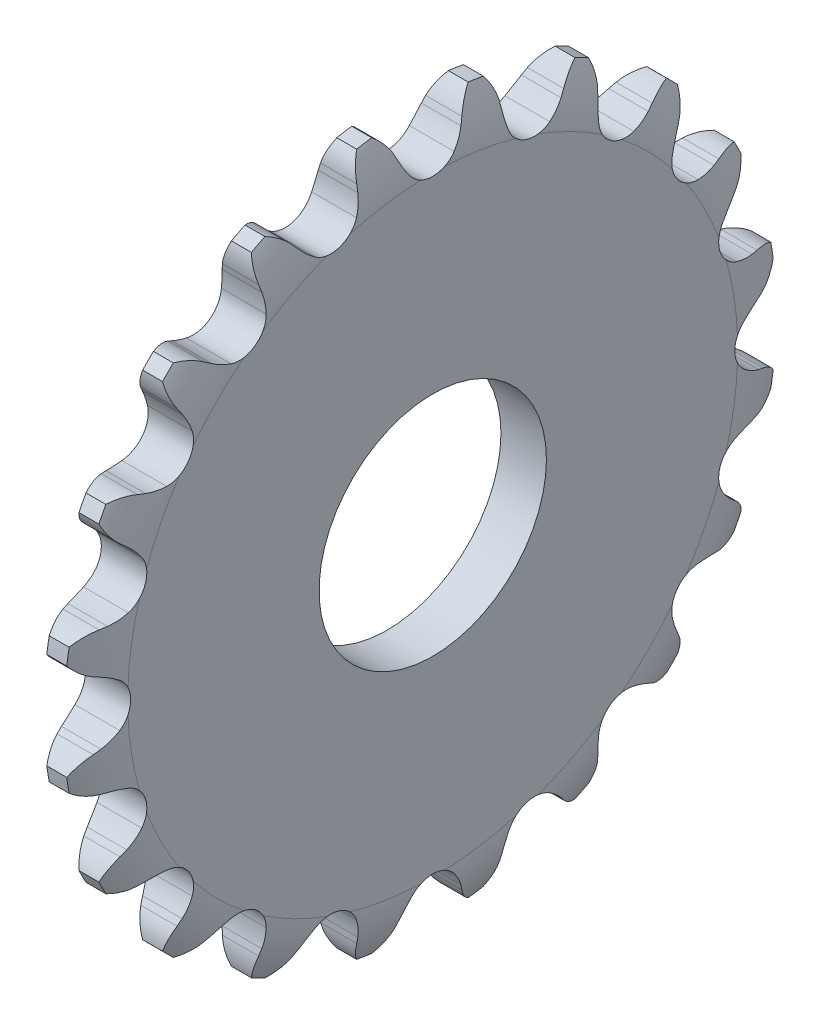
SolidWorks part; units mm, degrees
ref_plane "Plane1" through (0, 0, 0) normal (0, 0, 1) x (1, 0, 0)
ref_plane "Plane2" through (0, 0, 0) normal (0, 1, 0) x (1, 0, 0)
ref_plane "Plane3" through (0, 0, 0) normal (1, 0, 0) x (0, 0, -1)
other "Configuration Table"
sketch "Clipboard" plane through (0, 0, 0) normal (0, 1, 0) x (1, 0, 0)
  line L0 (0, 0) -> (5.967, -2.1718)
  line L1 (-15, 0) -> (100, 0) construction
  line L2 (0, 0) -> (-0.5218, 0.5897)
  line L3 (0, 0) -> (-2.9658, 1.1335)
  line L4 (0, 0) -> (2.9835, 1.0859)
  line L5 (0, 0) -> (-47.5972, -17.7524)
  line L6 (0, 0) -> (-2.3214, -1.5662)
  line L7 (-0.5218, 0.5897) -> (46.9042, 18.7948)
  line L8 (-76.2, 38.1) -> (-61.976, 38.1)
  line L9 (-73.2057, 38.5609) -> (-73.0533, 38.5634)
  line L10 (-73.0533, 76.1892) -> (-66.6525, 76.1892)
  circle A0 centre (0, 0) radius 1.651
  circle A1 centre (0, 0) radius 16.4902
  circle A2 centre (0, 0) radius 38.1
  dimension "Dr" = 3.302
  dimension "MHD" = 32.9803
  dimension "Hub_dia" = 76.2
  dimension "Num_teeth" = 20
  dimension "Pitch" = 6.35
  dimension "Width" = 3.175
  dimension "Chamfer_wid" = 0.7874
  dimension "Chamfer_dep" = 3.175
  dimension "Overall_len" = 50.8
  dimension "Show_teeth" = 20
  dimension "Thickness" = 2.8003
  dimension "OAL" = 50.8001
  dimension "T_dim" = 14.224
  dimension "Width_const" = 0.1524
  dimension "Width_factor" = 0.93
  dimension "Num_strands" = 1
  dimension "Transv_pitch" = 6.4008
sketch "BasProSke" plane through (0, 0, 0) normal (0, 1, 0) x (1, 0, 0)
  line L0 (-10, 0) -> (60, 0) construction
  line L1 (0, 0) -> (0, 18.7762)
  line L2 (0, 0) -> (2.8003, 0)
  line L3 (2.8003, 0) -> (2.8003, 18.7762)
  line L4 (2.0129, 21.9512) -> (0.7874, 21.9512)
  arc A0 (0, 18.7762) -> (0.7874, 21.9512) centre (6.7949, 18.7762) cw
  arc A1 (2.8003, 18.7762) -> (2.0129, 21.9512) centre (-3.9946, 18.7762) ccw
  dimension "Thickness" = 2.8003
  dimension "D1" = 6.7949
  dimension "G1" = 0.7874
  dimension "G2" = 0.7874
  dimension "H2" = 3.175
  dimension "H1" = 3.175
  dimension "Diameter" = 43.9023
revolve "Base-Revolve" add sketch "BasProSke" angle 360 about L0
sketch "GrvSke" plane through (0, 0, 0) normal (0, 1, 0) x (1, 0, 0)
  line L0 (2.8003, 18.7762) -> (2.8003, 16.4902)
  line L1 (2.8003, 16.4902) -> (6.4008, 16.4902)
  line L2 (6.4008, 16.4902) -> (6.4008, 18.7762)
  line L3 (2.0129, 21.9512) -> (7.1882, 21.9512)
  line L4 (4.6006, 0) -> (4.6006, 52.07) construction
  line L5 (-10, 0) -> (60, 0) construction
  line L6 (0, 0) -> (35.56, 0) construction
  arc A0 (6.4008, 18.7762) -> (7.1882, 21.9512) centre (13.1957, 18.7762) cw
  arc A1 (2.8003, 18.7762) -> (2.0129, 21.9512) centre (-3.9946, 18.7762) ccw
  dimension "G1" = 0.7874
  dimension "H1" = 3.175
  dimension "Diameter" = 43.9023
  dimension "Grv_diam" = 32.9803
  dimension "Grv_width" = 3.6004
  dimension "Offset" = 4.6006
revolve "Groove" [suppressed] cut sketch "GrvSke" angle 360 about L6
pattern_linear "Grooves" [suppressed]
sketch "TooCutSke" plane through (0, 0, 0) normal (1, 0, 0) x (0, 0, -1)
  line L0 (1.9183, 20.241) -> (2.0772, 20.619)
  line L1 (0, 0) -> (0, 107) construction
  line L2 (0, 20.296) -> (-10, 20.296) construction
  line L3 (-1.9183, 20.241) -> (-2.0772, 20.619)
  arc A0 (1.3375, 19.251) -> (1.9183, 20.241) centre (-2.0816, 21.9224) ccw
  arc A1 (1.3375, 19.251) -> (-1.3375, 19.251) centre (0, 20.296) cw
  arc A2 (2.0772, 20.619) -> (4.5659, 22.2725) centre (4.5659, 19.5729) cw
  arc A3 (-1.3375, 19.251) -> (-1.9183, 20.241) centre (2.0816, 21.9224) cw
  arc A4 (-2.0772, 20.619) -> (-4.5659, 22.2725) centre (-4.5659, 19.5729) ccw
  arc A5 (4.5659, 22.2725) -> (-4.5659, 22.2725) centre (0, 0) ccw
  dimension "R" = 1.6974
  dimension "E" = 4.339
  dimension "F" = 2.6996
  dimension "Pitch_radius" = 20.296
  dimension "W" = 4.5659
  dimension "V" = 0.7232
  dimension "A" = 38
  dimension "B" = 15.2
extrude "ToothCut" cut sketch "TooCutSke" along normal through all
pattern_circular "TeethCuts" count 20 every 18 about axis through (-10, 0, 0) along (1, 0, 0) of "ToothCut"
sketch "HubNeaOneSke" plane through (0, 0, 0) normal (-1, 0, 0) x (0, 0, 1)
  circle A0 centre (0, 0) radius 16.4902
  dimension "Diameter" = 32.9803
extrude "HubNearOne" [suppressed] add sketch "HubNeaOneSke" along normal blind 47.9997
sketch "HubNeaBotSke" plane through (0, 0, 0) normal (-1, 0, 0) x (0, 0, 1)
  circle A0 centre (0, 0) radius 16.4902
  dimension "Diameter" = 32.9803
extrude "HubNearBoth" [suppressed] add sketch "HubNeaBotSke" along normal blind 23.9999
ref_plane "FarPln" through (2.8003, 0, 0) normal (1, 0, 0) x (0, 0, -1)
sketch "HubFarSke" plane through (2.8003, 0, 0) normal (1, 0, 0) x (0, 0, -1)
  circle A0 centre (0, 0) radius 16.4902
  dimension "Diameter" = 32.9803
extrude "HubFar" [suppressed] add sketch "HubFarSke" along normal blind 23.9999
sketch "BorSke" plane through (0, 0, 0) normal (1, 0, 0) x (0, 0, -1)
  circle A0 centre (0, 0) radius 6.35
  dimension "Diameter" = 12.7
extrude "Bore" cut sketch "BorSke" along normal mid plane 101.6001
sketch "KeySke" plane through (0, 0, 0) normal (1, 0, 0) x (0, 0, -1)
  line L0 (-1.5875, 0) -> (-1.5875, 7.874)
  line L1 (-1.5875, 7.874) -> (1.5875, 7.874)
  line L2 (1.5875, 7.874) -> (1.5875, 0)
  line L3 (0, 0) -> (0, 34) construction
  line L4 (-1.5875, 0) -> (1.5875, 0)
  dimension "Width" = 3.175
  dimension "Offset" = 7.874
extrude "Keyway" [suppressed] cut sketch "KeySke" along normal mid plane 101.6001
pattern_circular "Keyway2" [suppressed] count 2 every 90 about axis through (-10, 0, 0) along (1, 0, 0)
sketch "Sketch1" plane through (0, 0, 0) normal (1, 0, 0) x (0, 0, -1)
  circle A0 centre (0, 0) radius 7
extrude "Bore 14 mm" cut sketch "Sketch1" against normal through all both and the other way through all both
equation "\"Num_teeth@Clipboard\" = int( \"Num_teeth@Clipboard\" )"
equation "\"Num_teeth@Clipboard\" = ((sgn( \"Num_teeth@Clipboard\" - 5.0)+1)*( \"Num_teeth@Clipboard\" - 5.0))/2 +5.0"
equation "\"Num_teeth@Clipboard\" = ((sgn( \"Num_teeth@Clipboard\" - 200.0)-1)*( \"Num_teeth@Clipboard\" - 200.0))/-2 +200.0"
equation "\"MHD@Clipboard\" = \"Pitch@Clipboard\" * (1.0 / tan(3.14159265 / \"Num_teeth@Clipboard\" ) - 1.0) - 0.03"
equation "\"Thickness@Clipboard\"  = \"Width@Clipboard\" * \"Width_factor@Clipboard\" - \"Width_const@Clipboard\" + (\"Num_strands@Clipboard\" - 1) * \"Transv_pitch@Clipboard\""
equation "\"OAL@Clipboard\" = \"Thickness@Clipboard\""
equation "\"MHD@Clipboard\" = ((sgn( \"MHD@Clipboard\" - \"Hub_dia@Clipboard\" )-1)*( \"MHD@Clipboard\" - \"Hub_dia@Clipboard\" ))/-2+ \"Hub_dia@Clipboard\""
equation "\"OAL@Clipboard\" = ((sgn( \"OAL@Clipboard\" - \"Overall_len@Clipboard\" )+1)*( \"OAL@Clipboard\" - \"Overall_len@Clipboard\" ))/2 + \"Overall_len@Clipboard\" + 0.000002"
equation "\"Num_teeth@TeethCuts\" = int( \"Show_teeth@Clipboard\" ) + 1"
equation "\"Num_teeth@TeethCuts\" = ((sgn( \"Num_teeth@TeethCuts\" - \"Num_teeth@Clipboard\" )-1)*( \"Num_teeth@TeethCuts\" - \"Num_teeth@Clipboard\" ))/-2+ \"Num_teeth@Clipboard\""
equation "\"Num_teeth@TeethCuts\" = ((sgn( \"Num_teeth@TeethCuts\" - 2.0)+1)*( \"Num_teeth@TeethCuts\" - 2.0))/2 +2.0"
equation "\"Angle@TeethCuts\" = 360.0 / \"Num_teeth@Clipboard\""
equation "\"Pitch_radius@TooCutSke\" = ( \"Pitch@Clipboard\" / 2.0) / sin(3.14159265 / \"Num_teeth@Clipboard\" )  'ma"
equation "\"R@TooCutSke\"  = \"Dr@Clipboard\" * 0.5025 + 0.0015"
equation "\"A@TooCutSke\" = 35.0 + (60.0 / \"Num_teeth@Clipboard\")"
equation "\"E@TooCutSke\"  = \"Dr@Clipboard\" * 1.3025 + 0.0015"
equation "\"B@TooCutSke\"  = 18.0 - (56.0 / \"Num_teeth@Clipboard\" )"
equation "\"W@TooCutSke\" = 1.4 * \"Dr@Clipboard\" * cos(3.14159265 / \"Num_teeth@Clipboard\" )"
equation "\"V@TooCutSke\" = 1.4 * \"Dr@Clipboard\" * sin(3.14159265 / \"Num_teeth@Clipboard\" )"
equation "\"Diameter@BasProSke\" = 2.0 * ( (0.3 * \"Pitch@Clipboard\" ) +  \"Pitch@Clipboard\" / 2.0 / tan(3.14159265 / \"Num_teeth@Clipboard\" ))"
equation "\"Thickness@BasProSke\"  = \"Thickness@Clipboard\""
equation "\"G1@BasProSke\" =  \"Chamfer_wid@Clipboard\""
equation "\"G2@BasProSke\" =  \"Chamfer_wid@Clipboard\""
equation "\"H1@BasProSke\" =  \"Chamfer_dep@Clipboard\""
equation "\"H2@BasProSke\" =  \"Chamfer_dep@Clipboard\""
equation "\"Diameter@GrvSke\" = \"Diameter@BasProSke\""
equation "\"G1@GrvSke\" = \"Chamfer_wid@Clipboard\""
equation "\"H1@GrvSke\" = \"Chamfer_dep@Clipboard\""
equation "\"Grv_diam@GrvSke\" =  \"Pitch@Clipboard\" * (1.0 / tan(3.14159265 / \"Num_teeth@Clipboard\" ) - 1.0) - 0.03"
equation "\"Grv_width@GrvSke\" =  \"Transv_pitch@Clipboard\" - ( \"Width@Clipboard\" * \"Width_factor@Clipboard\" - \"Width_const@Clipboard\" )"
equation "\"Offset@GrvSke\" = \"Grv_width@GrvSke\" / 2.0 + ( \"Width@Clipboard\" * \"Width_factor@Clipboard\" - \"Width_const@Clipboard\" )"
equation "\"Offset@Grooves\" = \"Transv_pitch@Clipboard\""
equation "\"Num_grvs@Grooves\" = \"Num_strands@Clipboard\""
equation "\"Num_grvs@Grooves\" = \"Num_grvs@Grooves\" - 1 * sgn( \"Num_grvs@Grooves\" -1)"
equation "\"Diameter@HubNeaOneSke\" = \"MHD@Clipboard\""
equation "\"Length@HubNearOne\" = \"OAL@Clipboard\" - \"Thickness@BasProSke\""
equation "\"Diameter@HubNeaBotSke\" = \"MHD@Clipboard\""
equation "\"Length@HubNearBoth\" = ( \"OAL@Clipboard\" - \"Thickness@BasProSke\" ) / 2.0"
equation "\"Thickness@FarPln\" = \"Thickness@BasProSke\""
equation "\"Diameter@HubFarSke\" = \"MHD@Clipboard\""
equation "\"Length@HubFar\" = ( \"OAL@Clipboard\" - \"Thickness@BasProSke\" ) / 2.0"
equation "\"D1@Bore\" = \"OAL@Clipboard\" * 2.0"
equation "\"D1@Keyway\" = \"OAL@Clipboard\" * 2.0"
equation "\"Offset@KeySke\" = \"T_dim@Clipboard\" - \"Diameter@BorSke\" / 2.0"
